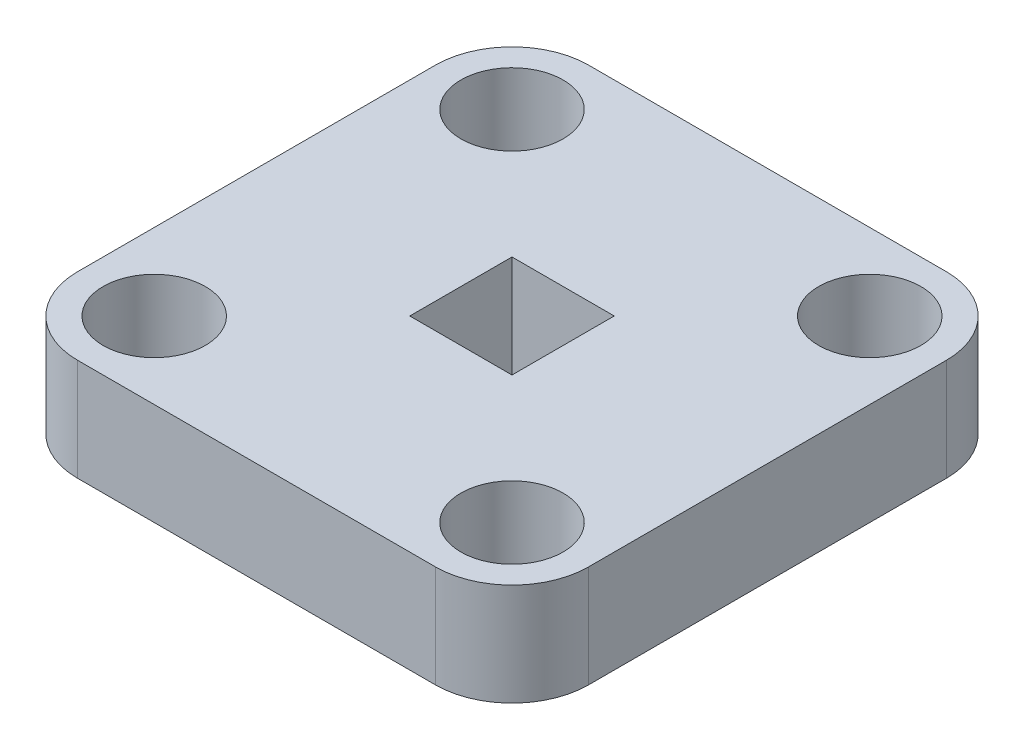
SolidWorks part; units mm, degrees
ref_plane "Front Plane" through (0, 0, 0) normal (0, 0, 1) x (1, 0, 0)
ref_plane "Top Plane" through (0, 0, 0) normal (0, 1, 0) x (1, 0, 0)
ref_plane "Right Plane" through (0, 0, 0) normal (1, 0, 0) x (0, 0, -1)
sketch "Sketch2" plane through (0, 0, 0) normal (0, 1, 0) x (1, 0, 0)
  line L1 (-10, 10) -> (10, 10)
  line L2 (-10, 10) -> (-10, -10)
  line L3 (-10, -10) -> (10, -10)
  line L4 (10, 10) -> (10, -10)
  line L10 (-2, 2) -> (2, 2)
  line L11 (-2, 2) -> (-2, -2)
  line L12 (-2, -2) -> (2, -2)
  line L13 (2, 2) -> (2, -2)
  line L14 (-2, 2) -> (2, -2) construction
  line L15 (-2, -2) -> (2, 2) construction
  circle A0 centre (-7, 7) radius 2
  circle A1 centre (7, 7) radius 2
  circle A2 centre (7, -7) radius 2
  circle A3 centre (-7, -7) radius 2
  point P4 (0, 0)
  dimension "D5" = 4
  dimension "D9" = 3
  dimension "D1" = 20
  dimension "D2" = 20
  dimension "D3" = 10
  dimension "D4" = 10
  dimension "D6" = 3
  dimension "D7" = 3
  dimension "D8" = 3
  dimension "D10" = 4
  dimension "D11" = 4
extrude "Boss-Extrude1" add sketch "Sketch2" along normal blind 4
fillet "Fillet3" radius 3 4 edges at (10, 2, 10) (10, 2, -10) (-10, 2, -10) (-10, 2, 10)
